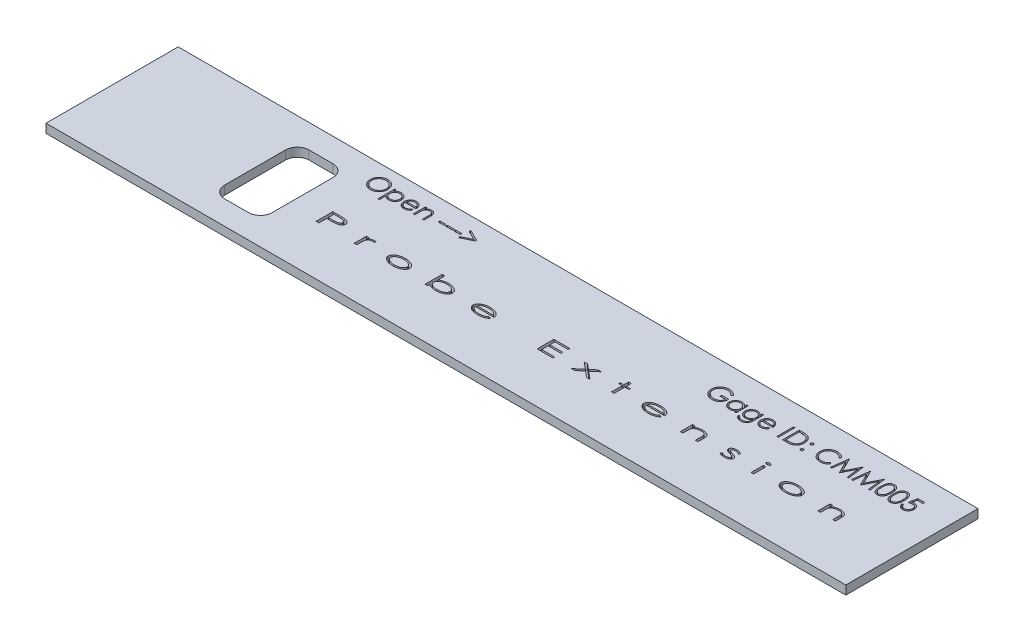
SolidWorks part; units mm, degrees
ref_plane "Front Plane" through (0, 0, 0) normal (0, 0, 1) x (1, 0, 0)
ref_plane "Top Plane" through (0, 0, 0) normal (0, 1, 0) x (1, 0, 0)
ref_plane "Right Plane" through (0, 0, 0) normal (1, 0, 0) x (0, 0, -1)
sketch "Sketch1" plane through (0, 0, 0) normal (0, 1, 0) x (1, 0, 0)
  line L1 (0, 0) -> (167.9, 0)
  line L2 (0, 0) -> (0, 27.75)
  line L3 (0, 27.75) -> (167.9, 27.75)
  line L4 (167.9, 0) -> (167.9, 27.75)
  dimension "D1" = 167.9
  dimension "D2" = 27.75
extrude "Boss-Extrude1" add sketch "Sketch1" along normal blind 1.85
sketch "Sketch2" plane through (0, 1.85, 0) normal (0, 1, 0) x (1, 0, 0)
  line L0 (167.9, 27.75) -> (0, 27.75) construction
  line L1 (30, 22.75) -> (40, 22.75)
  line L2 (30, 22.75) -> (30, 5)
  line L3 (30, 5) -> (40, 5)
  line L4 (40, 22.75) -> (40, 5)
  line L5 (0, 0) -> (167.9, 0) construction
  line L6 (0, 27.75) -> (0, 0) construction
  dimension "D1" = 5
  dimension "D2" = 5
  dimension "D3" = 10
  dimension "D4" = 30
extrude "Cut-Extrude1" cut sketch "Sketch2" against normal through all
fillet "Fillet1" radius 2.5 4 edges at (30, 0.925, -5) (40, 0.925, -5) (30, 0.925, -22.75) (40, 0.925, -22.75)
sketch "Sketch5" plane through (0, 1.85, 0) normal (0, 1, 0) x (1, 0, 0)
  text T0 "Open --->"
extrude "Cut-Extrude3" cut sketch "Sketch5" against normal blind 1.25
sketch "Sketch6" plane through (0, 1.85, 0) normal (0, 1, 0) x (1, 0, 0)
  text T0 "Gage ID: CMM005"
extrude "Cut-Extrude4" cut sketch "Sketch6" against normal blind 1.25
sketch "Sketch7" plane through (0, 1.85, 0) normal (0, 1, 0) x (1, 0, 0)
  text T0 "Probe Extension" font "Century Gothic" height 3.5
extrude "Cut-Extrude5" cut sketch "Sketch7" against normal blind 1.25
